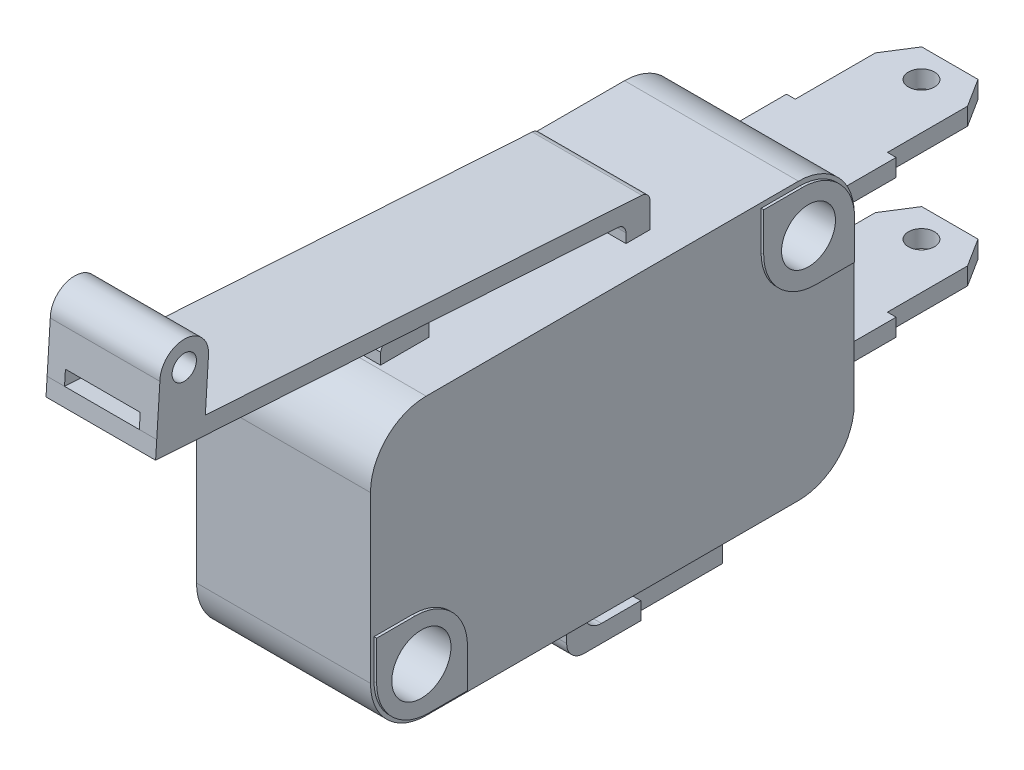
SolidWorks part; units mm, degrees
ref_plane "Front" through (0, 0, 0) normal (0, 0, 1) x (1, 0, 0)
ref_plane "Top" through (0, 0, 0) normal (0, 1, 0) x (1, 0, 0)
ref_plane "Right" through (0, 0, 0) normal (1, 0, 0) x (0, 0, -1)
ref_plane "Plane1" through (2.15, 0, 0) normal (1, 0, 0) x (0, 0, -1)
sketch "Sketch1" plane through (2.15, 0, 0) normal (1, 0, 0) x (0, 0, -1)
  line L0 (2.633, 8.9557) -> (4.0137, 8.9557)
  line L1 (4.0137, 8.9557) -> (4.0137, 9.8696)
  line L2 (4.0137, 9.8696) -> (-21.542, 11.5012)
  line L3 (-21.542, 11.5012) -> (-21.3542, 14.4868)
  line L4 (-24.1542, 14.4868) -> (-24.3363, 11.6796)
  line L5 (-24.3363, 11.6796) -> (-24.4, 10.6816)
  line L6 (-24.4, 10.6816) -> (2.633, 8.9557)
  arc A0 (-21.3542, 14.4868) -> (-24.1542, 14.4868) centre (-22.7542, 14.4868) ccw
extrude "Boss-Extrude1" add sketch "Sketch1" against normal blind 4.3
sketch "Sketch2" plane through (-2.15, 0, 0) normal (-1, 0, 0) x (0, 0, 1)
  line L0 (-2.633, 8.9557) -> (-4.0137, 8.9557)
  line L1 (-4.0137, 8.9557) -> (-4.0137, 9.8696)
  line L2 (-4.0137, 9.8696) -> (21.542, 11.5012)
  line L3 (21.542, 11.5012) -> (21.3542, 14.4868)
  line L4 (24.1542, 14.4868) -> (24.3363, 11.6796)
  line L5 (24.3363, 11.6796) -> (24.4, 10.6816)
  line L6 (24.4, 10.6816) -> (-2.633, 8.9557)
  arc A0 (21.3542, 14.4868) -> (24.1542, 14.4868) centre (22.7542, 14.4868) cw
extrude "Boss-Extrude2" add sketch "Sketch2" along normal blind 1
sketch "Sketch3" plane through (2.15, 0, 0) normal (1, 0, 0) x (0, 0, -1)
  line L0 (4.0137, 8.9557) -> (2.633, 8.9557)
  line L1 (2.633, 8.9557) -> (-24.4, 10.6816)
  line L2 (-24.4, 10.6816) -> (-24.3363, 11.6796)
  line L3 (-24.3363, 11.6796) -> (-24.1542, 14.4868)
  line L4 (-21.3542, 14.4868) -> (-21.542, 11.5012)
  line L5 (-21.542, 11.5012) -> (4.0137, 9.8696)
  line L6 (4.0137, 9.8696) -> (4.0137, 8.9557)
  arc A0 (-24.1542, 14.4868) -> (-21.3542, 14.4868) centre (-22.7542, 14.4868) cw
extrude "Boss-Extrude3" add sketch "Sketch3" along normal blind 1
sketch "Sketch4" plane through (2.15, 0, 0) normal (1, 0, 0) x (0, 0, -1)
  line L0 (-24.2825, 12.5084) -> (-24.3363, 11.6796)
  line L1 (-24.3363, 11.6796) -> (-21.542, 11.5012)
  line L2 (-21.542, 11.5012) -> (-21.4898, 12.3301)
  arc A0 (-21.4898, 12.3301) -> (-24.2825, 12.5084) centre (-22.7542, 14.4868) cw
extrude "Cut-Extrude1" cut sketch "Sketch4" against normal blind 4.3
sketch "Sketch5" plane through (-3.15, 0, 0) normal (-1, 0, 0) x (0, 0, 1)
  line L0 (-4.0137, 8.9557) -> (-4.0137, 9.8696)
  line L1 (-4.0137, 9.8696) -> (-2.633, 9.8696)
  line L2 (-2.633, 9.8696) -> (-2.633, 8.9557)
  line L3 (-2.633, 8.9557) -> (-4.0137, 8.9557)
extrude "Boss-Extrude4" add sketch "Sketch5" along normal blind 1.85
sketch "Sketch6" plane through (0, 8.9557, 0) normal (0, -1, 0) x (1, 0, 0)
  line L0 (-5, -4.0137) -> (-5, -2.633)
  line L1 (-5, -2.633) -> (3.15, -2.633)
  line L2 (3.15, -2.633) -> (3.15, -4.0137)
  line L3 (3.15, -4.0137) -> (-5, -4.0137)
extrude "Boss-Extrude5" add sketch "Sketch6" along normal blind 16.9057
sketch "Sketch7" plane through (0, 0, -4.0137) normal (0, 0, -1) x (-1, 0, 0)
  line L0 (-3.15, -7.95) -> (-3.15, 9.8696)
  line L1 (-3.15, 9.8696) -> (5, 9.8696)
  line L2 (5, 9.8696) -> (5, -7.95)
  line L3 (5, -7.95) -> (-3.15, -7.95)
extrude "Boss-Extrude6" add sketch "Sketch7" along normal blind 9.8863
sketch "Sketch8" plane through (0, 9.8696, 0) normal (0, 1, 0) x (-1, 0, 0)
  line L0 (5, -13.9) -> (5, -2.633)
  line L1 (5, -2.633) -> (3.15, -2.633)
  line L2 (3.15, -2.633) -> (3.15, -4.0137)
  line L3 (3.15, -4.0137) -> (-3.15, -4.0137)
  line L4 (-3.15, -4.0137) -> (-3.15, -13.9)
  line L5 (-3.15, -13.9) -> (5, -13.9)
extrude "Cut-Extrude2" cut sketch "Sketch8" against normal blind 0.9139
sketch "Sketch9" plane through (0, 8.9557, 0) normal (0, 1, 0) x (-1, 0, 0)
  line L0 (5, -13.9) -> (5, -2.633)
  line L1 (5, -2.633) -> (3.15, -2.633)
  line L2 (3.15, -2.633) -> (3.15, -4.0137)
  line L3 (3.15, -4.0137) -> (-3.15, -4.0137)
  line L4 (-3.15, -4.0137) -> (-3.15, -13.9)
  line L5 (-3.15, -13.9) -> (5, -13.9)
extrude "Cut-Extrude3" cut sketch "Sketch9" against normal blind 1.0057
sketch "Sketch10" plane through (0, 0, -2.633) normal (0, 0, 1) x (1, 0, 0)
  line L0 (3.15, 7.95) -> (3.15, -7.95)
  line L1 (3.15, -7.95) -> (-5, -7.95)
  line L2 (-5, -7.95) -> (-5, 7.95)
  line L3 (-5, 7.95) -> (3.15, 7.95)
extrude "Boss-Extrude7" add sketch "Sketch10" along normal blind 16.533
sketch "Sketch11" plane through (3.15, 0, 0) normal (1, 0, 0) x (0, 0, -1)
  line L0 (-13.9, 7.95) -> (13.9, 7.95)
  line L1 (13.9, 7.95) -> (13.9, -7.95)
  line L2 (13.9, -7.95) -> (-13.9, -7.95)
  line L3 (-13.9, -7.95) -> (-13.9, 7.95)
extrude "Boss-Extrude8" add sketch "Sketch11" along normal blind 1.85
sketch "Sketch12" plane through (0, -7.95, 0) normal (0, -1, 0) x (1, 0, 0)
  line L0 (-3.15, 0.775) -> (3.15, 0.775)
  line L1 (3.15, 0.775) -> (3.15, -0.225)
  line L2 (3.15, -0.225) -> (-3.15, -0.225)
  line L3 (-3.15, -0.225) -> (-3.15, 0.775)
extrude "Boss-Extrude9" add sketch "Sketch12" along normal blind 3.3
sketch "Sketch13" plane through (0, 0, -0.225) normal (0, 0, -1) x (-1, 0, 0)
  line L0 (-3.15, -10.25) -> (3.15, -10.25)
  line L1 (3.15, -10.25) -> (3.15, -11.25)
  line L2 (3.15, -11.25) -> (-3.15, -11.25)
  line L3 (-3.15, -11.25) -> (-3.15, -10.25)
extrude "Boss-Extrude10" add sketch "Sketch13" along normal blind 9.5
sketch "Sketch14" plane through (0, -10.25, 0) normal (0, 1, 0) x (-1, 0, 0)
  line L0 (3.15, -3.4862) -> (2.65, -3.4862)
  line L1 (2.65, -3.4862) -> (2.65, -9.725)
  line L2 (2.65, -9.725) -> (3.15, -9.725)
  line L3 (3.15, -9.725) -> (3.15, -3.4862)
extrude "Cut-Extrude4" cut sketch "Sketch14" against normal through all
sketch "Sketch15" plane through (0, -10.25, 0) normal (0, 1, 0) x (-1, 0, 0)
  line L0 (-2.65, -9.725) -> (-2.65, -3.4862)
  line L1 (-2.65, -3.4862) -> (-3.15, -3.4862)
  line L2 (-3.15, -3.4862) -> (-3.15, -9.725)
  line L3 (-3.15, -9.725) -> (-2.65, -9.725)
extrude "Cut-Extrude5" cut sketch "Sketch15" against normal through all
sketch "Sketch16" plane through (0, 0, -13.9) normal (0, 0, -1) x (-1, 0, 0)
  line L0 (3.15, 4.475) -> (3.15, 3.475)
  line L1 (3.15, 3.475) -> (-3.15, 3.475)
  line L2 (-3.15, 3.475) -> (-3.15, 4.475)
  line L3 (-3.15, 4.475) -> (3.15, 4.475)
extrude "Boss-Extrude11" add sketch "Sketch16" along normal blind 10.5
sketch "Sketch17" plane through (0, 3.475, 0) normal (0, -1, 0) x (1, 0, 0)
  line L0 (3.15, -18.1612) -> (2.65, -18.1612)
  line L1 (2.65, -18.1612) -> (2.65, -24.4)
  line L2 (2.65, -24.4) -> (3.15, -24.4)
  line L3 (3.15, -24.4) -> (3.15, -18.1612)
extrude "Cut-Extrude6" cut sketch "Sketch17" against normal through all
sketch "Sketch18" plane through (0, 3.475, 0) normal (0, -1, 0) x (1, 0, 0)
  line L0 (-3.15, -24.4) -> (-2.65, -24.4)
  line L1 (-2.65, -24.4) -> (-2.65, -18.1612)
  line L2 (-2.65, -18.1612) -> (-3.15, -18.1612)
  line L3 (-3.15, -18.1612) -> (-3.15, -24.4)
extrude "Cut-Extrude7" cut sketch "Sketch18" against normal through all
sketch "Sketch19" plane through (0, 0, -13.9) normal (0, 0, -1) x (-1, 0, 0)
  line L0 (3.15, -3.475) -> (3.15, -4.475)
  line L1 (3.15, -4.475) -> (-3.15, -4.475)
  line L2 (-3.15, -4.475) -> (-3.15, -3.475)
  line L3 (-3.15, -3.475) -> (3.15, -3.475)
extrude "Boss-Extrude12" add sketch "Sketch19" along normal blind 10.5
sketch "Sketch20" plane through (0, -4.475, 0) normal (0, -1, 0) x (1, 0, 0)
  line L0 (3.15, -18.1612) -> (2.65, -18.1612)
  line L1 (2.65, -18.1612) -> (2.65, -24.4)
  line L2 (2.65, -24.4) -> (3.15, -24.4)
  line L3 (3.15, -24.4) -> (3.15, -18.1612)
extrude "Cut-Extrude8" cut sketch "Sketch20" against normal through all
sketch "Sketch21" plane through (0, -4.475, 0) normal (0, -1, 0) x (1, 0, 0)
  line L0 (-3.15, -24.4) -> (-2.65, -24.4)
  line L1 (-2.65, -24.4) -> (-2.65, -18.1612)
  line L2 (-2.65, -18.1612) -> (-3.15, -18.1612)
  line L3 (-3.15, -18.1612) -> (-3.15, -24.4)
extrude "Cut-Extrude9" cut sketch "Sketch21" against normal through all
sketch "Sketch22" plane through (-5, 0, 0) normal (-1, 0, 0) x (0, 0, 1)
  line L0 (-8.55, 2.45) -> (-13.775, 2.45)
  line L1 (-13.775, 2.45) -> (-13.775, 7.675)
  line L2 (-13.775, 7.675) -> (-8.55, 7.675)
  line L3 (-8.55, 7.675) -> (-8.55, 2.45)
extrude "Boss-Extrude13" add sketch "Sketch22" along normal blind 0.15
sketch "Sketch23" plane through (-5, 0, 0) normal (-1, 0, 0) x (0, 0, 1)
  line L0 (13.7, -7.75) -> (8.475, -7.75)
  line L1 (8.475, -7.75) -> (8.475, -2.525)
  line L2 (8.475, -2.525) -> (13.7, -2.525)
  line L3 (13.7, -2.525) -> (13.7, -7.75)
extrude "Boss-Extrude14" add sketch "Sketch23" along normal blind 0.15
ref_plane "Plane2" through (-2.15, 0, 0) normal (-1, 0, 0) x (0, -1, 0)
sketch "Sketch24" plane through (-2.15, 0, 0) normal (-1, 0, 0) x (0, -1, 0)
  line L0 (-8.6, 7.675) -> (-7.95, 7.675)
  line L1 (-7.95, 7.675) -> (-7.95, 10.475)
  line L2 (-7.95, 10.475) -> (-8.6, 10.475)
  arc A0 (-8.6, 10.475) -> (-8.6, 7.675) centre (-8.12, 9.075) ccw
extrude "Boss-Extrude15" add sketch "Sketch24" against normal blind 4.3
sketch "Sketch25" plane through (5, 0, 0) normal (1, 0, 0) x (0, 0, -1)
  line L0 (-13.7, -7.75) -> (-13.7, -2.525)
  line L1 (-13.7, -2.525) -> (-8.475, -2.525)
  line L2 (-8.475, -2.525) -> (-8.475, -7.75)
  line L3 (-8.475, -7.75) -> (-13.7, -7.75)
extrude "Boss-Extrude16" add sketch "Sketch25" along normal blind 0.15
sketch "Sketch26" plane through (5, 0, 0) normal (1, 0, 0) x (0, 0, -1)
  line L0 (8.55, 2.45) -> (8.55, 7.675)
  line L1 (8.55, 7.675) -> (13.775, 7.675)
  line L2 (13.775, 7.675) -> (13.775, 2.45)
  line L3 (13.775, 2.45) -> (8.55, 2.45)
extrude "Boss-Extrude17" add sketch "Sketch26" along normal blind 0.15
hole_wizard "#00 Clearance Hole1" positions "Sketch28" profile "Sketch27" hole size "#00" standard "ANSI Inch"
sketch "Sketch28" plane through (0, -4.475, 0) normal (0, -1, 0) x (-1, 0, 0)
  point P0 (0, 22.7671)
sketch "Sketch27" plane through (0, -4.475, -22.7671) normal (1, 0, 0) x (0, 0, -1)
  line L0 (0, 0) -> (0, 1)
  line L1 (0, 1) -> (0.75, 1)
  line L2 (0.75, 1) -> (0.75, 0)
  line L5 (0.75, 0) -> (0, 0)
  line L11 (0, -6.35) -> (0, 107.95) construction
  dimension "Thru Hole Dia." = 1.5
  dimension "Thru Hole Depth" = 1
hole_wizard "#00 Clearance Hole2" positions "Sketch30" profile "Sketch29" hole size "#00" standard "ANSI Inch"
sketch "Sketch30" plane through (0, 4.475, 0) normal (0, 1, 0) x (1, 0, 0)
  point P0 (0, 22.7671)
sketch "Sketch29" plane through (0, 4.475, -22.7671) normal (1, 0, 0) x (0, 0, 1)
  line L0 (0, 0) -> (0, 15.725)
  line L1 (0, 15.725) -> (0.75, 15.725)
  line L2 (0.75, 15.725) -> (0.75, 0)
  line L5 (0.75, 0) -> (0, 0)
  line L11 (0, -6.35) -> (0, 107.95) construction
  dimension "Thru Hole Dia." = 1.5
  dimension "Thru Hole Depth" = 15.725
hole_wizard "#4 Clearance Hole1" positions "Sketch32" profile "Sketch31" hole size "#4" standard "ANSI Inch"
sketch "Sketch32" plane through (5.15, 0, 0) normal (1, 0, 0) x (0, 0, -1)
  point P0 (11.125, 5.1)
sketch "Sketch31" plane through (5.15, 5.1, -11.125) normal (0, 1, 0) x (0, 0, -1)
  line L0 (0, 0) -> (0, 10.3)
  line L1 (0, 10.3) -> (1.55, 10.3)
  line L2 (1.55, 10.3) -> (1.55, 0)
  line L5 (1.55, 0) -> (0, 0)
  line L11 (0, -6.35) -> (0, 107.95) construction
  dimension "Thru Hole Dia." = 3.1
  dimension "Thru Hole Depth" = 10.3
hole_wizard "#4 Clearance Hole2" positions "Sketch34" profile "Sketch33" hole size "#4" standard "ANSI Inch"
sketch "Sketch34" plane through (5.15, 0, 0) normal (1, 0, 0) x (0, 0, -1)
  point P0 (-11.125, -5.1)
sketch "Sketch33" plane through (5.15, -5.1, 11.125) normal (0, 1, 0) x (0, 0, -1)
  line L0 (0, 0) -> (0, 10.3)
  line L1 (0, 10.3) -> (1.7, 10.3)
  line L2 (1.7, 10.3) -> (1.7, 0)
  line L5 (1.7, 0) -> (0, 0)
  line L11 (0, -6.35) -> (0, 107.95) construction
  dimension "Thru Hole Dia." = 3.4
  dimension "Thru Hole Depth" = 10.3
hole_wizard "#00 Clearance Hole3" positions "Sketch36" profile "Sketch35" hole size "#00" standard "ANSI Inch"
sketch "Sketch36" plane through (0, -10.25, 0) normal (0, 1, 0) x (1, 0, 0)
  point P0 (0, 8.0921)
sketch "Sketch35" plane through (0, -10.25, -8.0921) normal (1, 0, 0) x (0, 0, 1)
  line L0 (0, 0) -> (0, 1)
  line L1 (0, 1) -> (0.75, 1)
  line L2 (0.75, 1) -> (0.75, 0)
  line L5 (0.75, 0) -> (0, 0)
  line L11 (0, -6.35) -> (0, 107.95) construction
  dimension "Thru Hole Dia." = 1.5
  dimension "Thru Hole Depth" = 1
hole_wizard "#00 Clearance Hole4" positions "Sketch38" profile "Sketch37" hole size "#00" standard "ANSI Inch"
sketch "Sketch38" plane through (3.15, 0, 0) normal (1, 0, 0) x (0, 0, -1)
  point P0 (-22.7542, 14.4868)
sketch "Sketch37" plane through (3.15, 14.4868, 22.7542) normal (0, 1, 0) x (0, 0, -1)
  line L0 (0, 0) -> (0, 1)
  line L1 (0, 1) -> (0.7, 1)
  line L2 (0.7, 1) -> (0.7, 0)
  line L5 (0.7, 0) -> (0, 0)
  line L10 (0, 1) -> (-0.7, 1) construction
  line L11 (0, -6.35) -> (0, 107.95) construction
  dimension "Hole Dia." = 1.4
  dimension "Hole Depth" = 1
  dimension "Drill Angle" = 180
hole_wizard "#00 Clearance Hole5" positions "Sketch40" profile "Sketch39" hole size "#00" standard "ANSI Inch"
sketch "Sketch40" plane through (-3.15, 0, 0) normal (-1, 0, 0) x (0, 0, 1)
  point P0 (22.7542, 14.4868)
sketch "Sketch39" plane through (-3.15, 14.4868, 22.7542) normal (0, 1, 0) x (0, 0, 1)
  line L0 (0, 0) -> (0, 1)
  line L1 (0, 1) -> (0.7, 1)
  line L2 (0.7, 1) -> (0.7, 0)
  line L5 (0.7, 0) -> (0, 0)
  line L10 (0, 1) -> (-0.7, 1) construction
  line L11 (0, -6.35) -> (0, 107.95) construction
  dimension "Hole Dia." = 1.4
  dimension "Hole Depth" = 1
  dimension "Drill Angle" = 180
ref_plane "Plane3" through (0, 0, 0) normal (-1, 0, 0) x (0, -1, 0)
sketch "Sketch41" plane through (0, 0, 0) normal (-1, 0, 0) x (0, -1, 0)
  arc A0 (-12.5084, 24.2825) -> (-12.3301, 21.4898) centre (-14.4868, 22.7542) ccw
chamfer "Chamfer1" distance 1.6329 angle 32.32 2 edges at (-2.65, -3.975, -24.4) (-2.65, 3.975, -24.4)
chamfer "Chamfer2" distance 1.033 angle 57.68 2 edges at (2.65, 3.975, -24.4) (2.65, -3.975, -24.4)
chamfer "Chamfer3" distance 1.6329 angle 32.32 2 edges at (2.65, -10.75, -9.725) (-2.65, -10.75, -9.725)
fillet "Fillet1" radius 0.5 2 edges
fillet "Fillet2" radius 1 2 edges at (0, -10.25, -0.225) (0, -11.25, 0.775)
fillet "Fillet3" radius 3 8 edges at (5.075, 2.45, -8.55) (-5.075, 7.675, -13.775) (-5.075, -2.525, 8.475) (-5.075, -7.75, 13.7) (5.075, 7.675, -13.775) (5.075, -2.525, 8.475) (5.075, -7.75, 13.7) (-5.075, 2.45, -8.55)
fillet "Fillet4" radius 3.2 4 edges at (0, -7.95, 13.9) (0, 7.95, 13.9) (0, -7.95, -13.9) (0, 7.95, -13.9)
